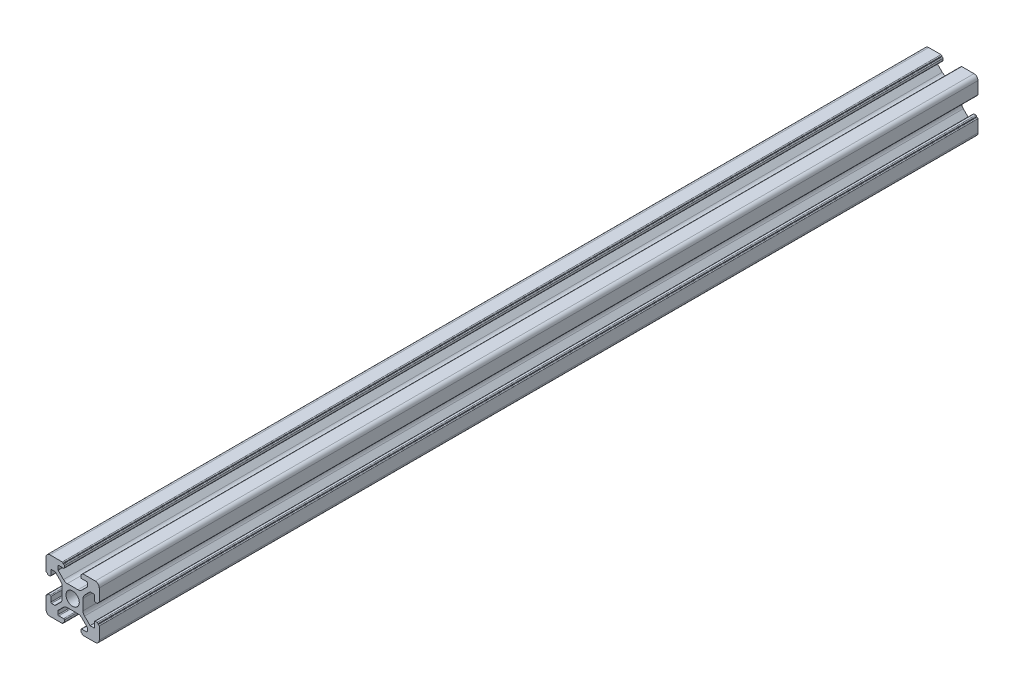
SolidWorks part; units mm, degrees
material "6063-T6，棒材(SS)"
ref_plane "前视基准面" through (0, 0, 0) normal (0, 0, 1) x (1, 0, 0)
ref_plane "上视基准面" through (0, 0, 0) normal (0, 1, 0) x (1, 0, 0)
ref_plane "右视基准面" through (0, 0, 0) normal (1, 0, 0) x (0, 0, -1)
sketch "中心线" plane through (0, 0, 0) normal (0, 0, 1) x (1, 0, 0)
  line L0 (7912.3831, 177.422) -> (7917.3831, 177.422) construction
  line L1 (7914.8831, 174.922) -> (7914.8831, 179.922) construction
sketch "截面" plane through (0, 0, 0) normal (0, 0, 1) x (1, 0, 0)
  line L0 (3961.9273, 92.1361) -> (3963.9144, 94.1231)
  line L1 (3964.1265, 94.211) -> (3965.3416, 94.211)
  line L2 (3965.6416, 93.911) -> (3965.6416, 92.111)
  line L3 (3965.9416, 91.811) -> (3966.6416, 91.811)
  line L4 (3966.9416, 92.111) -> (3966.9416, 92.311)
  line L5 (3966.9416, 92.311) -> (3967.1416, 92.311)
  line L6 (3967.4416, 92.611) -> (3967.4416, 97.211)
  line L7 (3965.9416, 98.711) -> (3961.3416, 98.711)
  line L8 (3961.0416, 98.411) -> (3961.0416, 98.211)
  line L9 (3961.0416, 98.211) -> (3960.8416, 98.211)
  line L10 (3960.5416, 97.911) -> (3960.5416, 97.211)
  line L11 (3960.8416, 96.911) -> (3962.6416, 96.911)
  line L12 (3962.9416, 96.611) -> (3962.9416, 95.3959)
  line L13 (3962.8537, 95.1838) -> (3960.8667, 93.1968)
  line L14 (3959.4525, 92.611) -> (3955.4306, 92.611)
  line L15 (3954.0164, 93.1968) -> (3952.0294, 95.1838)
  line L16 (3951.9416, 95.3959) -> (3951.9416, 96.611)
  line L17 (3952.2416, 96.911) -> (3954.0416, 96.911)
  line L18 (3954.3416, 97.211) -> (3954.3416, 97.911)
  line L19 (3954.0416, 98.211) -> (3953.8416, 98.211)
  line L20 (3953.8416, 98.211) -> (3953.8416, 98.411)
  line L21 (3953.5416, 98.711) -> (3948.9416, 98.711)
  line L22 (3947.4416, 97.211) -> (3947.4416, 92.611)
  line L23 (3947.7416, 92.311) -> (3947.9416, 92.311)
  line L24 (3947.9416, 92.311) -> (3947.9416, 92.111)
  line L25 (3948.2416, 91.811) -> (3948.9416, 91.811)
  line L26 (3949.2416, 92.111) -> (3949.2416, 93.911)
  line L27 (3949.5416, 94.211) -> (3950.7566, 94.211)
  line L28 (3950.9688, 94.1231) -> (3952.9558, 92.1361)
  line L29 (3953.5416, 90.7219) -> (3953.5416, 86.7001)
  line L30 (3952.9558, 85.2859) -> (3950.9688, 83.2989)
  line L31 (3950.7566, 83.211) -> (3949.5416, 83.211)
  line L32 (3949.2416, 83.511) -> (3949.2416, 85.311)
  line L33 (3948.9416, 85.611) -> (3948.2416, 85.611)
  line L34 (3947.9416, 85.311) -> (3947.9416, 85.111)
  line L35 (3947.9416, 85.111) -> (3947.7416, 85.111)
  line L36 (3947.4416, 84.811) -> (3947.4416, 80.211)
  line L37 (3948.9416, 78.711) -> (3953.5416, 78.711)
  line L38 (3954.3416, 79.511) -> (3954.3416, 80.211)
  line L39 (3954.0416, 80.511) -> (3952.2416, 80.511)
  line L40 (3951.9416, 80.811) -> (3951.9416, 82.0261)
  line L41 (3952.0294, 82.2382) -> (3954.0164, 84.2252)
  line L42 (3955.4306, 84.811) -> (3959.4525, 84.811)
  line L43 (3960.8667, 84.2252) -> (3962.8537, 82.2382)
  line L44 (3962.9416, 82.0261) -> (3962.9416, 80.811)
  line L45 (3962.6416, 80.511) -> (3960.8416, 80.511)
  line L46 (3960.5416, 80.211) -> (3960.5416, 79.511)
  line L47 (3961.3416, 78.711) -> (3965.9416, 78.711)
  line L48 (3967.4416, 80.211) -> (3967.4416, 84.811)
  line L49 (3967.1416, 85.111) -> (3966.9416, 85.111)
  line L50 (3966.9416, 85.111) -> (3966.9416, 85.311)
  line L51 (3966.6416, 85.611) -> (3965.9416, 85.611)
  line L52 (3965.6416, 85.311) -> (3965.6416, 83.511)
  line L53 (3965.3416, 83.211) -> (3964.0022, 83.211)
  line L54 (3964.0022, 83.211) -> (3961.9273, 85.2859)
  line L55 (3961.3416, 86.7001) -> (3961.3416, 90.7219)
  circle A0 centre (3957.4416, 88.711) radius 2.5
  arc A1 (3964.1265, 94.211) -> (3963.9144, 94.1231) centre (3964.1265, 93.911) ccw
  arc A2 (3965.6416, 93.911) -> (3965.3416, 94.211) centre (3965.3416, 93.911) ccw
  arc A3 (3965.6416, 92.111) -> (3965.9416, 91.811) centre (3965.9416, 92.111) ccw
  arc A4 (3966.6416, 91.811) -> (3966.9416, 92.111) centre (3966.6416, 92.111) ccw
  arc A5 (3967.1416, 92.311) -> (3967.4416, 92.611) centre (3967.1416, 92.611) ccw
  arc A6 (3967.4416, 97.211) -> (3965.9416, 98.711) centre (3965.9416, 97.211) ccw
  arc A7 (3961.3416, 98.711) -> (3961.0416, 98.411) centre (3961.3416, 98.411) ccw
  arc A8 (3960.8416, 98.211) -> (3960.5416, 97.911) centre (3960.8416, 97.911) ccw
  arc A9 (3960.5416, 97.211) -> (3960.8416, 96.911) centre (3960.8416, 97.211) ccw
  arc A10 (3962.9416, 96.611) -> (3962.6416, 96.911) centre (3962.6416, 96.611) ccw
  arc A11 (3962.8537, 95.1838) -> (3962.9416, 95.3959) centre (3962.6416, 95.3959) ccw
  arc A12 (3959.4525, 92.611) -> (3960.8667, 93.1968) centre (3959.4525, 94.611) ccw
  arc A13 (3954.0164, 93.1968) -> (3955.4306, 92.611) centre (3955.4306, 94.611) ccw
  arc A14 (3951.9416, 95.3959) -> (3952.0294, 95.1838) centre (3952.2416, 95.3959) ccw
  arc A15 (3952.2416, 96.911) -> (3951.9416, 96.611) centre (3952.2416, 96.611) ccw
  arc A16 (3954.0416, 96.911) -> (3954.3416, 97.211) centre (3954.0416, 97.211) ccw
  arc A17 (3954.3416, 97.911) -> (3954.0416, 98.211) centre (3954.0416, 97.911) ccw
  arc A18 (3953.8416, 98.411) -> (3953.5416, 98.711) centre (3953.5416, 98.411) ccw
  arc A19 (3948.9416, 98.711) -> (3947.4416, 97.211) centre (3948.9416, 97.211) ccw
  arc A20 (3947.4416, 92.611) -> (3947.7416, 92.311) centre (3947.7416, 92.611) ccw
  arc A21 (3947.9416, 92.111) -> (3948.2416, 91.811) centre (3948.2416, 92.111) ccw
  arc A22 (3948.9416, 91.811) -> (3949.2416, 92.111) centre (3948.9416, 92.111) ccw
  arc A23 (3949.5416, 94.211) -> (3949.2416, 93.911) centre (3949.5416, 93.911) ccw
  arc A24 (3950.9688, 94.1231) -> (3950.7566, 94.211) centre (3950.7566, 93.911) ccw
  arc A25 (3953.5416, 90.7219) -> (3952.9558, 92.1361) centre (3951.5416, 90.7219) ccw
  arc A26 (3952.9558, 85.2859) -> (3953.5416, 86.7001) centre (3951.5416, 86.7001) ccw
  arc A27 (3950.7566, 83.211) -> (3950.9688, 83.2989) centre (3950.7566, 83.511) ccw
  arc A28 (3949.2416, 83.511) -> (3949.5416, 83.211) centre (3949.5416, 83.511) ccw
  arc A29 (3949.2416, 85.311) -> (3948.9416, 85.611) centre (3948.9416, 85.311) ccw
  arc A30 (3948.2416, 85.611) -> (3947.9416, 85.311) centre (3948.2416, 85.311) ccw
  arc A31 (3947.7416, 85.111) -> (3947.4416, 84.811) centre (3947.7416, 84.811) ccw
  arc A32 (3947.4416, 80.211) -> (3948.9416, 78.711) centre (3948.9416, 80.211) ccw
  arc A33 (3953.5416, 78.711) -> (3953.8416, 79.011) centre (3953.5416, 79.011) ccw
  arc A34 (3954.0416, 79.211) -> (3953.8416, 79.011) centre (3954.0416, 79.011) ccw
  arc A35 (3954.0416, 79.211) -> (3954.3416, 79.511) centre (3954.0416, 79.511) ccw
  arc A36 (3954.3416, 80.211) -> (3954.0416, 80.511) centre (3954.0416, 80.211) ccw
  arc A37 (3951.9416, 80.811) -> (3952.2416, 80.511) centre (3952.2416, 80.811) ccw
  arc A38 (3952.0294, 82.2382) -> (3951.9416, 82.0261) centre (3952.2416, 82.0261) ccw
  arc A39 (3955.4306, 84.811) -> (3954.0164, 84.2252) centre (3955.4306, 82.811) ccw
  arc A40 (3960.8667, 84.2252) -> (3959.4525, 84.811) centre (3959.4525, 82.811) ccw
  arc A41 (3962.9416, 82.0261) -> (3962.8537, 82.2382) centre (3962.6416, 82.0261) ccw
  arc A42 (3962.6416, 80.511) -> (3962.9416, 80.811) centre (3962.6416, 80.811) ccw
  arc A43 (3960.8416, 80.511) -> (3960.5416, 80.211) centre (3960.8416, 80.211) ccw
  arc A44 (3960.5416, 79.511) -> (3960.8416, 79.211) centre (3960.8416, 79.511) ccw
  arc A45 (3961.0416, 79.011) -> (3960.8416, 79.211) centre (3960.8416, 79.011) ccw
  arc A46 (3961.0416, 79.011) -> (3961.3416, 78.711) centre (3961.3416, 79.011) ccw
  arc A47 (3965.9416, 78.711) -> (3967.4416, 80.211) centre (3965.9416, 80.211) ccw
  arc A48 (3967.4416, 84.811) -> (3967.1416, 85.111) centre (3967.1416, 84.811) ccw
  arc A49 (3966.9416, 85.311) -> (3966.6416, 85.611) centre (3966.6416, 85.311) ccw
  arc A50 (3965.9416, 85.611) -> (3965.6416, 85.311) centre (3965.9416, 85.311) ccw
  arc A51 (3965.3416, 83.211) -> (3965.6416, 83.511) centre (3965.3416, 83.511) ccw
  arc A52 (3961.3416, 86.7001) -> (3961.9273, 85.2859) centre (3963.3416, 86.7001) ccw
  arc A53 (3961.9273, 92.1361) -> (3961.3416, 90.7219) centre (3963.3416, 90.7219) ccw
  dimension "D1" = 20
extrude "凸台-拉伸1" add sketch "截面" along normal blind 330
